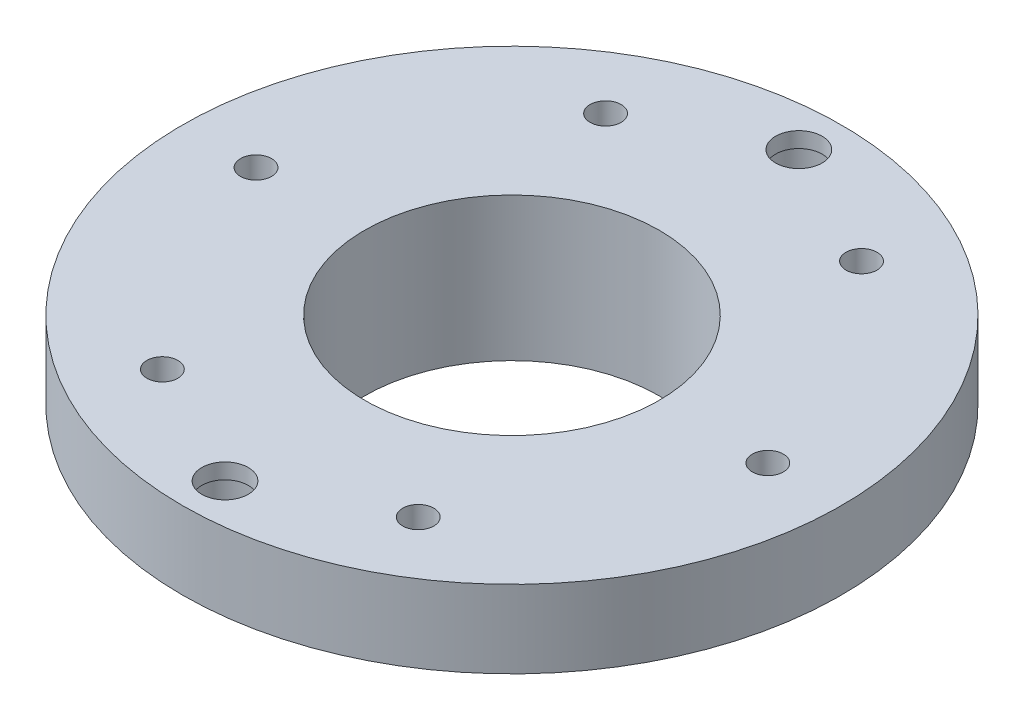
SolidWorks part; units mm, degrees
material "Like ABS"
ref_plane "Front Plane" through (0, 0, 0) normal (0, 0, 1) x (1, 0, 0)
ref_plane "Top Plane" through (0, 0, 0) normal (0, 1, 0) x (1, 0, 0)
ref_plane "Right Plane" through (0, 0, 0) normal (1, 0, 0) x (0, 0, -1)
sketch "Sketch1" plane through (0, 0, 0) normal (0, 1, 0) x (1, 0, 0)
  circle A0 centre (0, 0) radius 21.25
  dimension "D1" = 42.5
extrude "Boss-Extrude1" add sketch "Sketch1" along normal blind 5
sketch "Sketch2" plane through (0, 5, 0) normal (0, 1, 0) x (1, 0, 0)
  line L0 (0, 0) -> (0, 18.5) construction
  circle A0 centre (0, 18.5) radius 1.5
  dimension "D2" = 3
  dimension "D1" = 18.5
extrude "Cut-Extrude1" cut sketch "Sketch2" against normal up to surface (5 mm away) up to face at (0, 0, 21.25)
sketch "Sketch3" plane through (0, 0, 0) normal (0, -1, 0) x (1, 0, 0)
  circle A0 centre (0, -18.5) radius 2
  dimension "D1" = 4
extrude "Cut-Extrude2" cut sketch "Sketch3" against normal blind 4
pattern_circular "CirPattern1" count 2 over 360 about axis through (0, 0, 0) along (0, 1, 0) of "Cut-Extrude2", "Cut-Extrude1"
sketch "Sketch5" plane through (0, 0, 0) normal (0, -1, 0) x (1, 0, 0)
  circle A0 centre (0, 0) radius 14
  dimension "D1" = 28
extrude "Boss-Extrude2" add sketch "Sketch5" along normal blind 0.25
sketch "Sketch6" plane through (0, -0.25, 0) normal (0, -1, 0) x (1, 0, 0)
  circle A0 centre (0, 0) radius 12.575
  dimension "D1" = 25.15
extrude "Boss-Extrude3" add sketch "Sketch6" along normal blind 4
chamfer "Chamfer1" distance 0.5 angle 45 1 edges at (0, -4.25, -12.575)
sketch "Sketch7" plane through (0, -4.25, 0) normal (0, -1, 0) x (1, 0, 0)
  circle A0 centre (0, 0) radius 9.5
  dimension "D1" = 19
extrude "Cut-Extrude3" cut sketch "Sketch7" against normal up to surface (9.25 mm away) up to face at (0, 5, 17)
sketch "Sketch8" plane through (0, 5, 0) normal (0, 1, 0) x (1, 0, 0)
  line L0 (0, 16.5) -> (0, 0) construction
  line L1 (0, 0) -> (8.25, 14.2894) construction
  circle A0 centre (8.25, 14.2894) radius 1
  dimension "D2" = 2
  dimension "D1" = 30
  dimension "D3" = 16.5
extrude "Cut-Extrude4" cut sketch "Sketch8" against normal blind 4
pattern_circular "CirPattern2" count 6 over 360 about axis through (0, 0, 0) along (0, 1, 0) of "Cut-Extrude4"
